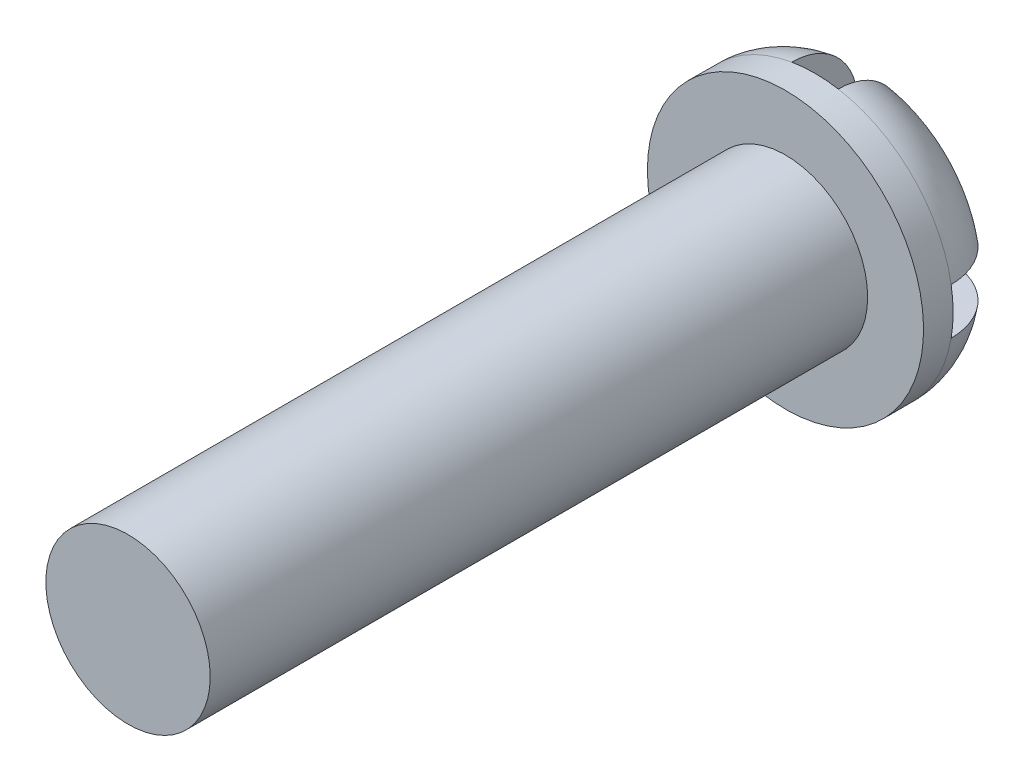
SolidWorks part; units mm, degrees
ref_plane "前视基准面" through (0, 0, 0) normal (0, 0, 1) x (1, 0, 0)
ref_plane "上视基准面" through (0, 0, 0) normal (0, 1, 0) x (1, 0, 0)
ref_plane "右视基准面" through (0, 0, 0) normal (1, 0, 0) x (0, 0, -1)
sketch "草图1" plane through (0, 0, 0) normal (0, 0, 1) x (1, 0, 0)
  circle A0 centre (0, 0) radius 2.5
  dimension "D1" = 5
extrude "凸台-拉伸1" add sketch "草图1" along normal blind 20
sketch "草图2" plane through (0, 0, 0) normal (0, 0, -1) x (-1, 0, 0)
  circle A0 centre (0, 0) radius 4.2
  dimension "D1" = 8.4
extrude "凸台-拉伸2" add sketch "草图2" along normal blind 2.9
fillet "圆角1" radius 2 1 edges at (-4.2, 0, -2.9)
sketch "草图3" plane through (0, 0, -2.9) normal (0, 0, -1) x (-1, 0, 0)
  line L0 (-0.7071, 0.7071) -> (-0.7071, 6.0064)
  line L1 (1, -1) -> (-1, -1) construction
  line L2 (1, -1) -> (1, 1) construction
  line L3 (1, 1) -> (-1, 1) construction
  line L4 (-1, -1) -> (-1, 1) construction
  line L5 (1, -1) -> (-1, 1) construction
  line L6 (1, 1) -> (-1, -1) construction
  line L7 (0.7071, 0.7071) -> (0.7071, 6.0064)
  line L8 (0.7071, 6.0064) -> (-0.7071, 6.0064)
  line L9 (0.7071, 0.7071) -> (6.0064, 0.7071)
  line L10 (0.7071, -0.7071) -> (6.0064, -0.7071)
  line L11 (6.0064, -0.7071) -> (6.0064, 0.7071)
  line L12 (0.7071, -0.7071) -> (0.7071, -6.0064)
  line L13 (-0.7071, -0.7071) -> (-0.7071, -6.0064)
  line L14 (-0.7071, -6.0064) -> (0.7071, -6.0064)
  line L15 (-0.7071, -0.7071) -> (-6.0064, -0.7071)
  line L16 (-0.7071, 0.7071) -> (-6.0064, 0.7071)
  line L17 (-6.0064, 0.7071) -> (-6.0064, -0.7071)
  circle A0 centre (0, 0) radius 1 construction
  dimension "D1" = 4
extrude "切除-拉伸1" cut sketch "草图3" against normal blind 2
